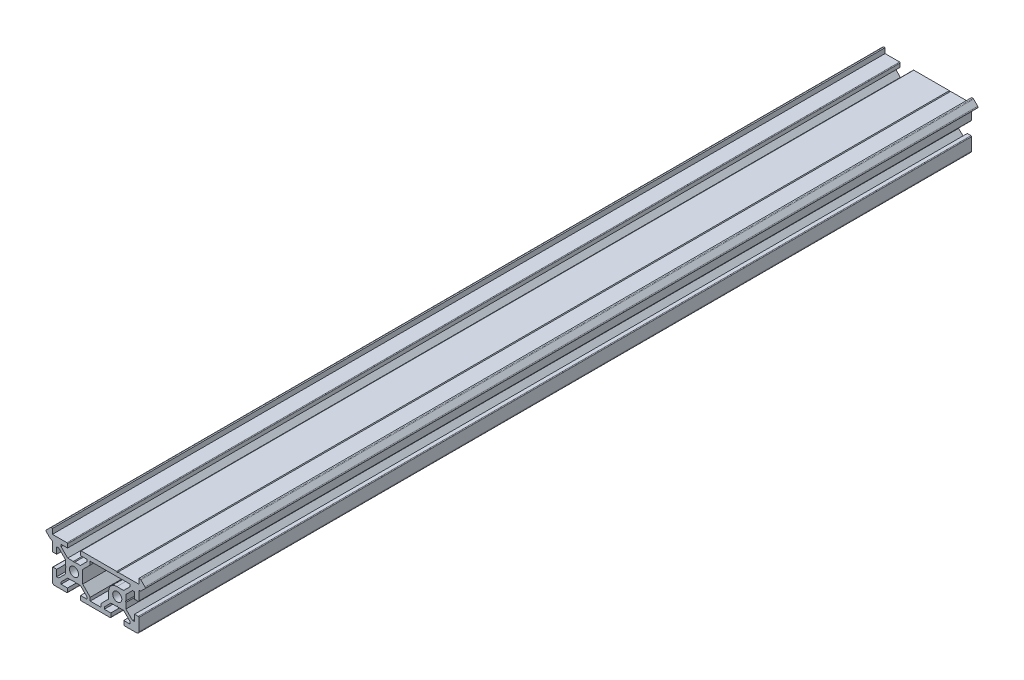
SolidWorks part; units mm, degrees
ref_plane "Front Plane" through (0, 0, 0) normal (0, 0, 1) x (1, 0, 0)
ref_plane "Top Plane" through (0, 0, 0) normal (0, 1, 0) x (1, 0, 0)
ref_plane "Right Plane" through (0, 0, 0) normal (1, 0, 0) x (0, 0, -1)
sketch "Model" plane through (0, 0, 0) normal (0, 0, 1) x (1, 0, 0)
  line L0 (0, 0) -> (0, 76.2) construction
  line L1 (0, 0) -> (101.6, 0) construction
  line L2 (0, 76.2) -> (101.6, 76.2) construction
  line L3 (101.6, 0) -> (101.6, 76.2) construction
  line L4 (28.7715, 48.1056) -> (30.6465, 49.9806)
  line L5 (31.5929, 50.127) -> (31.5929, 47.752)
  line L6 (31.5929, 44.877) -> (31.5929, 41.052)
  line L7 (31.5929, 34.452) -> (31.5929, 28.752)
  line L8 (33.5929, 31.752) -> (33.5929, 34.752)
  line L9 (33.5929, 40.752) -> (33.5929, 43.752)
  line L10 (35.5929, 29.752) -> (35.5929, 30.6914)
  line L11 (35.5929, 44.8127) -> (35.5929, 45.752)
  line L12 (37.5929, 40.6914) -> (37.5929, 38.052)
  line L13 (37.5929, 37.452) -> (37.5929, 34.8127)
  line L14 (38.5929, 28.052) -> (38.5929, 29.752)
  line L15 (38.5929, 45.752) -> (38.5929, 47.452)
  line L16 (32.5929, 27.752) -> (38.2929, 27.752)
  line L17 (44.8929, 27.752) -> (58.2929, 27.752)
  line L18 (64.8929, 27.752) -> (70.5929, 27.752)
  line L19 (37.5929, 38.052) -> (37.8929, 37.752)
  line L20 (41.5929, 34.052) -> (41.8929, 33.752)
  line L21 (30.6465, 45.5235) -> (28.7715, 47.3985)
  line L22 (41.8929, 41.752) -> (41.5929, 41.452)
  line L23 (37.8929, 37.752) -> (37.5929, 37.452)
  line L24 (67.5929, 29.752) -> (64.5929, 29.752)
  line L25 (58.5929, 29.752) -> (55.5929, 29.752)
  line L26 (54.0929, 29.752) -> (49.0929, 29.752)
  line L27 (47.5929, 29.752) -> (44.5929, 29.752)
  line L28 (38.5929, 29.752) -> (35.5929, 29.752)
  line L29 (34.5323, 43.752) -> (37.5929, 40.6914)
  line L30 (44.5323, 33.752) -> (47.5929, 30.6914)
  line L31 (44.5929, 47.452) -> (44.5929, 45.752)
  line L32 (44.5929, 29.752) -> (44.5929, 28.052)
  line L33 (47.5929, 44.8127) -> (44.5323, 41.752)
  line L34 (37.5929, 34.8127) -> (34.5323, 31.752)
  line L35 (69.5929, 31.752) -> (68.6536, 31.752)
  line L36 (34.5323, 31.752) -> (33.5929, 31.752)
  line L37 (49.0929, 31.3127) -> (45.5929, 34.8127)
  line L38 (38.6536, 41.752) -> (35.5929, 44.8127)
  line L39 (45.5929, 34.8127) -> (45.5929, 40.6914)
  line L40 (35.5929, 30.6914) -> (38.6536, 33.752)
  line L41 (45.5929, 40.6914) -> (49.0929, 44.1914)
  line L42 (38.6536, 33.752) -> (41.2929, 33.752)
  line L43 (41.8929, 33.752) -> (44.5323, 33.752)
  line L44 (58.6536, 33.752) -> (61.2929, 33.752)
  line L45 (61.8929, 33.752) -> (64.5323, 33.752)
  line L46 (41.5929, 41.452) -> (41.2929, 41.752)
  line L47 (47.5929, 45.752) -> (47.5929, 44.8127)
  line L48 (47.5929, 30.6914) -> (47.5929, 29.752)
  line L49 (41.2929, 33.752) -> (41.5929, 34.052)
  line L50 (71.2929, 34.752) -> (69.5929, 34.752)
  line L51 (33.5929, 34.752) -> (31.8929, 34.752)
  line L52 (49.0929, 29.752) -> (49.0929, 31.3127)
  line L53 (49.0929, 44.1914) -> (49.0929, 45.752)
  line L54 (61.5929, 47.452) -> (61.8929, 47.752)
  line L55 (31.8929, 40.752) -> (33.5929, 40.752)
  line L56 (69.5929, 40.752) -> (71.2929, 40.752)
  line L57 (54.0929, 31.3127) -> (54.0929, 29.752)
  line L58 (64.5323, 41.752) -> (61.4029, 41.752)
  line L59 (44.5323, 41.752) -> (41.8929, 41.752)
  line L60 (41.2929, 41.752) -> (38.6536, 41.752)
  line L61 (61.5929, 34.052) -> (61.8929, 33.752)
  line L62 (55.5929, 29.752) -> (55.5929, 30.6914)
  line L63 (33.5929, 43.752) -> (34.5323, 43.752)
  line L64 (68.6536, 43.752) -> (69.5929, 43.752)
  line L65 (57.5929, 37.942) -> (57.5929, 34.8127)
  line L66 (58.5929, 28.052) -> (58.5929, 29.752)
  line L67 (31.0929, 45.377) -> (31, 45.377)
  line L68 (72.0929, 45.377) -> (72.1858, 45.377)
  line L69 (35.5929, 45.752) -> (38.5929, 45.752)
  line L70 (44.5929, 45.752) -> (47.5929, 45.752)
  line L71 (49.0929, 45.752) -> (67.5929, 45.752)
  line L72 (64.5323, 33.752) -> (67.5929, 30.6914)
  line L73 (68.6536, 31.752) -> (65.5929, 34.8127)
  line L74 (67.5929, 44.8127) -> (64.5323, 41.752)
  line L75 (57.5929, 34.8127) -> (54.0929, 31.3127)
  line L76 (55.5929, 30.6914) -> (58.6536, 33.752)
  line L77 (65.5929, 40.6914) -> (68.6536, 43.752)
  line L78 (72.5394, 45.5235) -> (74.4144, 47.3985)
  line L79 (71.5929, 47.752) -> (61.8929, 47.752)
  line L80 (61.2929, 47.752) -> (44.8929, 47.752)
  line L81 (38.2929, 47.752) -> (31.5929, 47.752)
  line L82 (65.5929, 37.452) -> (65.2929, 37.752)
  line L83 (61.2929, 33.752) -> (61.5929, 34.052)
  line L84 (65.2929, 37.752) -> (65.5929, 38.052)
  line L85 (72.1858, 50.127) -> (71.5929, 50.127)
  line L86 (31, 50.127) -> (31.5929, 50.127)
  line L87 (64.5929, 29.752) -> (64.5929, 28.052)
  line L88 (61.2929, 47.752) -> (61.5929, 47.452)
  line L89 (65.5929, 34.8127) -> (65.5929, 37.452)
  line L90 (65.5929, 38.052) -> (65.5929, 40.6914)
  line L91 (67.5929, 45.752) -> (67.5929, 44.8127)
  line L92 (67.5929, 30.6914) -> (67.5929, 29.752)
  line L93 (69.5929, 43.752) -> (69.5929, 40.752)
  line L94 (69.5929, 34.752) -> (69.5929, 31.752)
  line L95 (71.5929, 50.127) -> (71.5929, 47.752)
  line L96 (71.5929, 28.752) -> (71.5929, 34.452)
  line L97 (71.5929, 41.052) -> (71.5929, 44.877)
  line L98 (74.4144, 48.1056) -> (72.5394, 49.9806)
  arc A0 (61.4029, 41.752) -> (57.5929, 37.942) centre (61.4029, 37.942) ccw
  circle A1 centre (61.5929, 37.752) radius 2.1
  circle A2 centre (41.5929, 37.752) radius 2.1
  arc A3 (31.5929, 28.752) -> (32.5929, 27.752) centre (32.5929, 28.752) ccw
  arc A4 (70.5929, 27.752) -> (71.5929, 28.752) centre (70.5929, 28.752) ccw
  arc A5 (31.5929, 44.877) -> (31.0929, 45.377) centre (31.0929, 44.877) ccw
  arc A6 (72.0929, 45.377) -> (71.5929, 44.877) centre (72.0929, 44.877) ccw
  arc A7 (31, 50.127) -> (30.6465, 49.9806) centre (31, 49.627) ccw
  arc A8 (28.7715, 48.1056) -> (28.7715, 47.3985) centre (29.125, 47.752) ccw
  arc A9 (30.6465, 45.5235) -> (31, 45.377) centre (31, 45.877) ccw
  arc A10 (72.5394, 49.9806) -> (72.1858, 50.127) centre (72.1858, 49.627) ccw
  arc A11 (74.4144, 47.3985) -> (74.4144, 48.1056) centre (74.0608, 47.752) ccw
  arc A12 (72.1858, 45.377) -> (72.5394, 45.5235) centre (72.1858, 45.877) ccw
  arc A13 (31.8929, 34.752) -> (31.5929, 34.452) centre (31.8929, 34.452) ccw
  arc A14 (44.8929, 47.752) -> (44.5929, 47.452) centre (44.8929, 47.452) ccw
  arc A15 (38.5929, 47.452) -> (38.2929, 47.752) centre (38.2929, 47.452) ccw
  arc A16 (31.5929, 41.052) -> (31.8929, 40.752) centre (31.8929, 41.052) ccw
  arc A17 (38.2929, 27.752) -> (38.5929, 28.052) centre (38.2929, 28.052) ccw
  arc A18 (44.5929, 28.052) -> (44.8929, 27.752) centre (44.8929, 28.052) ccw
  arc A19 (58.2929, 27.752) -> (58.5929, 28.052) centre (58.2929, 28.052) ccw
  arc A20 (64.5929, 28.052) -> (64.8929, 27.752) centre (64.8929, 28.052) ccw
  arc A21 (71.5929, 34.452) -> (71.2929, 34.752) centre (71.2929, 34.452) ccw
  arc A22 (71.2929, 40.752) -> (71.5929, 41.052) centre (71.2929, 41.052) ccw
extrude "Boss-Extrude1" add sketch "Model" along normal up to surface (385.1698 mm away)
ref_plane "Plane1" through (51.5929, 0, 0) normal (-1, 0, 0) x (0, 0, 1)
